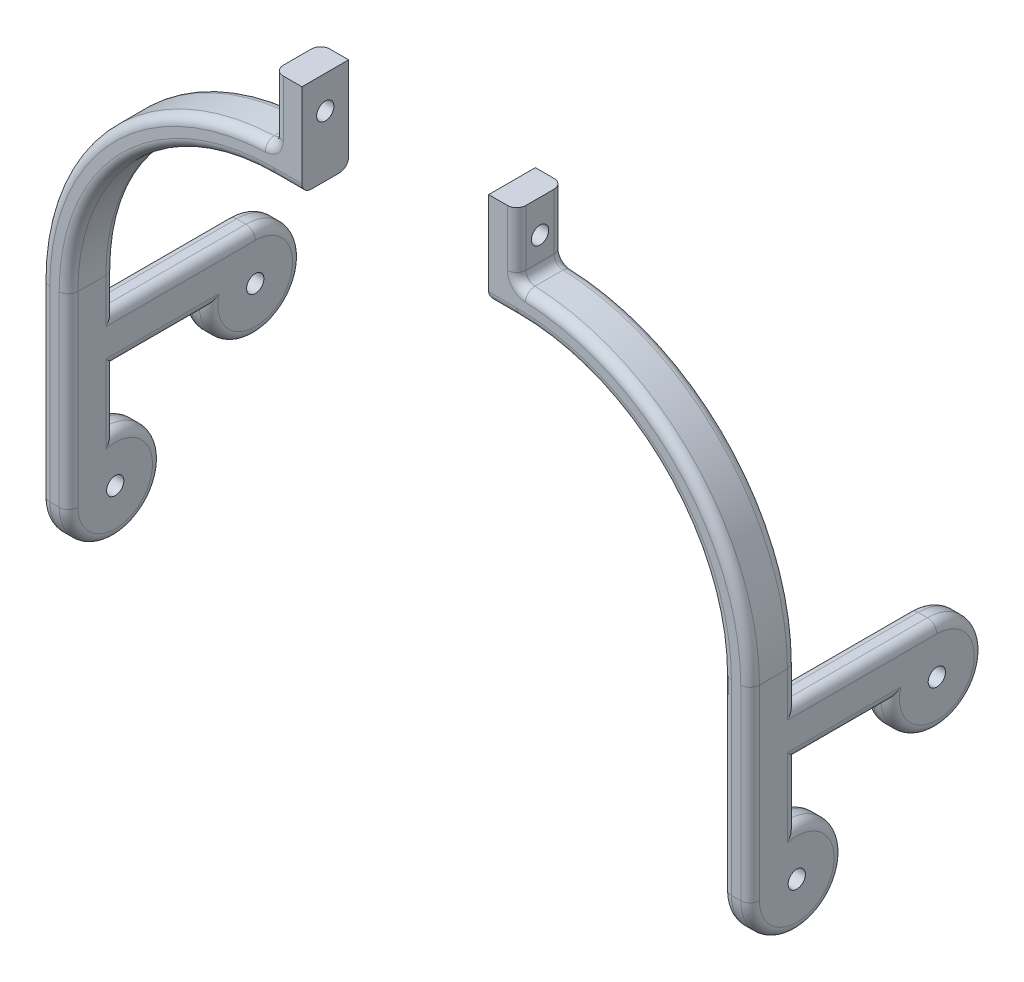
SolidWorks part; units mm, degrees
ref_plane "Front Plane" through (0, 0, 0) normal (0, 0, 1) x (1, 0, 0)
ref_plane "Top Plane" through (0, 0, 0) normal (0, 1, 0) x (1, 0, 0)
ref_plane "Right Plane" through (0, 0, 0) normal (1, 0, 0) x (0, 0, -1)
sketch "Sketch1" plane through (0, 0, 0) normal (0, 0, 1) x (1, 0, 0)
  line L0 (0, 0) -> (0, 20)
  line L1 (0, 20) -> (-6, 20)
  line L2 (-6, 20) -> (-6, 6)
  line L3 (-6, 6) -> (-56, 6) construction
  line L4 (-56, 6) -> (-56, -44) construction
  line L5 (0, 0) -> (-6, 0)
  line L6 (-56, -44) -> (-56, -84)
  line L7 (-56, -84) -> (-50, -84)
  line L8 (-50, -84) -> (-50, -44)
  line L9 (20, 0) -> (20, 38.7643) construction
  line L10 (0, 0) -> (40, 0) construction
  line L11 (96, -84) -> (90, -84)
  line L12 (96, -44) -> (96, -84)
  line L13 (46, 20) -> (46, 6)
  line L14 (40, 20) -> (46, 20)
  line L15 (40, 0) -> (40, 20)
  line L16 (40, 0) -> (46, 0)
  line L17 (90, -84) -> (90, -44)
  arc A0 (-6, 6) -> (-56, -44) centre (-6, -44) ccw
  arc A1 (-6, 0) -> (-50, -44) centre (-6, -44) ccw
  arc A2 (46, 6) -> (96, -44) centre (46, -44) cw
  arc A3 (46, 0) -> (90, -44) centre (46, -44) cw
  dimension "D1" = 20
  dimension "D7" = 44
  dimension "D2" = 6
  dimension "D3" = 14
  dimension "D4" = 50
  dimension "D5" = 50
  dimension "D6" = 50
  dimension "D8" = 40
  dimension "D9" = 6
  dimension "D10" = 40
extrude "Boss-Extrude2" add sketch "Sketch1" along normal blind 10
sketch "Sketch2" plane through (46, 0, 0) normal (1, 0, 0) x (0, 0, -1)
  line L0 (-10, 20) -> (0, 6) construction
  circle A0 centre (-5, 13) radius 1.85
  dimension "D1" = 3.7
extrude "Cut-Extrude1" cut sketch "Sketch2" against normal through all both and the other way through all
sketch "Sketch5" plane through (-56, 0, 0) normal (-1, 0, 0) x (0, 0, 1)
  circle A0 centre (0, -84) radius 10
extrude "Boss-Extrude5" add sketch "Sketch5" against normal blind 6
sketch "Sketch6" plane through (-56, 0, 0) normal (-1, 0, 0) x (0, 0, 1)
  line L0 (10, -44) -> (0, -59) construction
  line L1 (0, -44) -> (0, -74) construction
  line L2 (5, -51.5) -> (0, -51.5) construction
  line L4 (0, -51.5) -> (-30, -51.5)
  line L5 (0, -51.5) -> (0, -61.5)
  line L6 (0, -61.5) -> (-30, -61.5)
  line L7 (-30, -51.5) -> (-30, -61.5)
  dimension "D1" = 10
  dimension "D2" = 30
extrude "Boss-Extrude6" add sketch "Sketch6" against normal blind 6
sketch "Sketch7" plane through (-56, 0, 0) normal (-1, 0, 0) x (0, 0, 1)
  circle A0 centre (-30, -61.5) radius 10
extrude "Boss-Extrude7" add sketch "Sketch7" against normal blind 6
sketch "Sketch8" plane through (96, 0, 0) normal (1, 0, 0) x (0, 0, -1)
  line L0 (-10, -44) -> (0, -64) construction
  line L1 (0, -84) -> (0, -44) construction
  line L2 (0, -64) -> (-5, -54) construction
  line L3 (-5, -54) -> (0, -54) construction
  circle A0 centre (0, -84) radius 10
extrude "Boss-Extrude10" add sketch "Sketch8" against normal blind 6 contours A0
sketch "Sketch13" plane through (96, 0, 0) normal (1, 0, 0) x (0, 0, -1)
  line L0 (-10, -44) -> (0, -61.5) construction
  line L1 (0, -61.5) -> (-5, -52.75) construction
  line L2 (-5, -52.75) -> (0, -52.75) construction
  line L3 (0, -74) -> (0, -44) construction
  line L5 (0, -51.5) -> (30, -51.5)
  line L6 (0, -51.5) -> (0, -61.5)
  line L7 (0, -61.5) -> (30, -61.5)
  line L8 (30, -51.5) -> (30, -61.5)
  dimension "D1" = 30
  dimension "D2" = 10
extrude "Boss-Extrude13" add sketch "Sketch13" against normal blind 6
sketch "Sketch14" plane through (96, 0, 0) normal (1, 0, 0) x (0, 0, -1)
  circle A0 centre (30, -61.5) radius 10
extrude "Boss-Extrude14" add sketch "Sketch14" against normal blind 6
sketch "Sketch15" plane through (-56, 0, 0) normal (-1, 0, 0) x (0, 0, 1)
  circle A0 centre (-30, -61.5) radius 1.85
  circle A1 centre (0, -84) radius 1.85
extrude "Cut-Extrude4" cut sketch "Sketch15" against normal through all both and the other way through all
fillet "Fillet2" radius 2 12 edges at (90, -51.5, -15) (43, 0, 10) (90, -91.0711, -7.0711) (90, -64, 10) (43, 0, 0) (90, -47.75, 0) (40, 0, 5) (90, -67.75, 0) (90, -61.5, -10) (90, -68.5711, -37.0711) (77.1127, -12.8873, 10) (77.1127, -12.8873, 0)
fillet "Fillet3" radius 2 12 edges at (46, 13, 10) (46, 13, 0) (96, -47.75, 0) (81.3553, -8.6447, 10) (96, -64, 10) (96, -68.5711, -37.0711) (46, 6, 5) (81.3553, -8.6447, 0) (96, -91.0711, -7.0711) (96, -67.75, 0) (96, -61.5, -10) (96, -51.5, -15)
fillet "Fillet4" radius 2 12 edges at (-6, 13, 10) (-6, 13, 0) (-56, -91.0711, -7.0711) (-56, -64, 10) (-56, -47.75, 0) (-56, -68.5711, -37.0711) (-6, 6, 5) (-41.3553, -8.6447, 10) (-41.3553, -8.6447, 0) (-56, -51.5, -15) (-56, -61.5, -10) (-56, -67.75, 0)
fillet "Fillet5" radius 2 11 edges at (-50, -51.5, -15) (-50, -91.0711, -7.0711) (-50, -64, 10) (-3, 0, 10) (-50, -47.75, 0) (-3, 0, 0) (-50, -68.5711, -37.0711) (-50, -67.75, 0) (-50, -61.5, -10) (-37.1127, -12.8873, 10) (-37.1127, -12.8873, 0)
